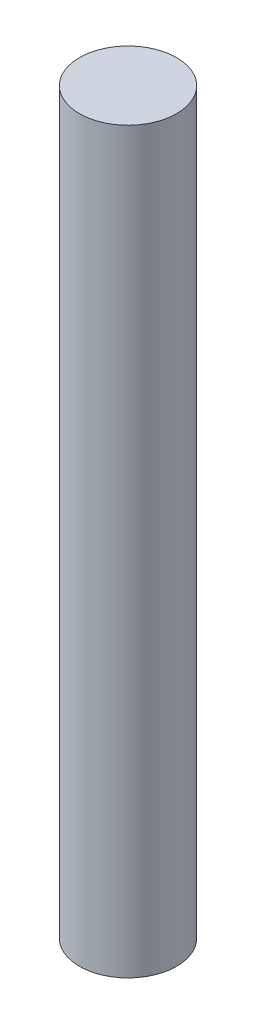
SolidWorks part; units mm, degrees
material "AISI 1020"
ref_plane "Front Plane" through (0, 0, 0) normal (0, 0, 1) x (1, 0, 0)
ref_plane "Top Plane" through (0, 0, 0) normal (0, 1, 0) x (1, 0, 0)
ref_plane "Right Plane" through (0, 0, 0) normal (1, 0, 0) x (0, 0, -1)
sketch "Sketch1" plane through (0, 0, 0) normal (0, 1, 0) x (1, 0, 0)
  circle A0 centre (0, 0) radius 6.35
  dimension "D1" = 12.7
extrude "Boss-Extrude1" add sketch "Sketch1" along normal blind 96.52
